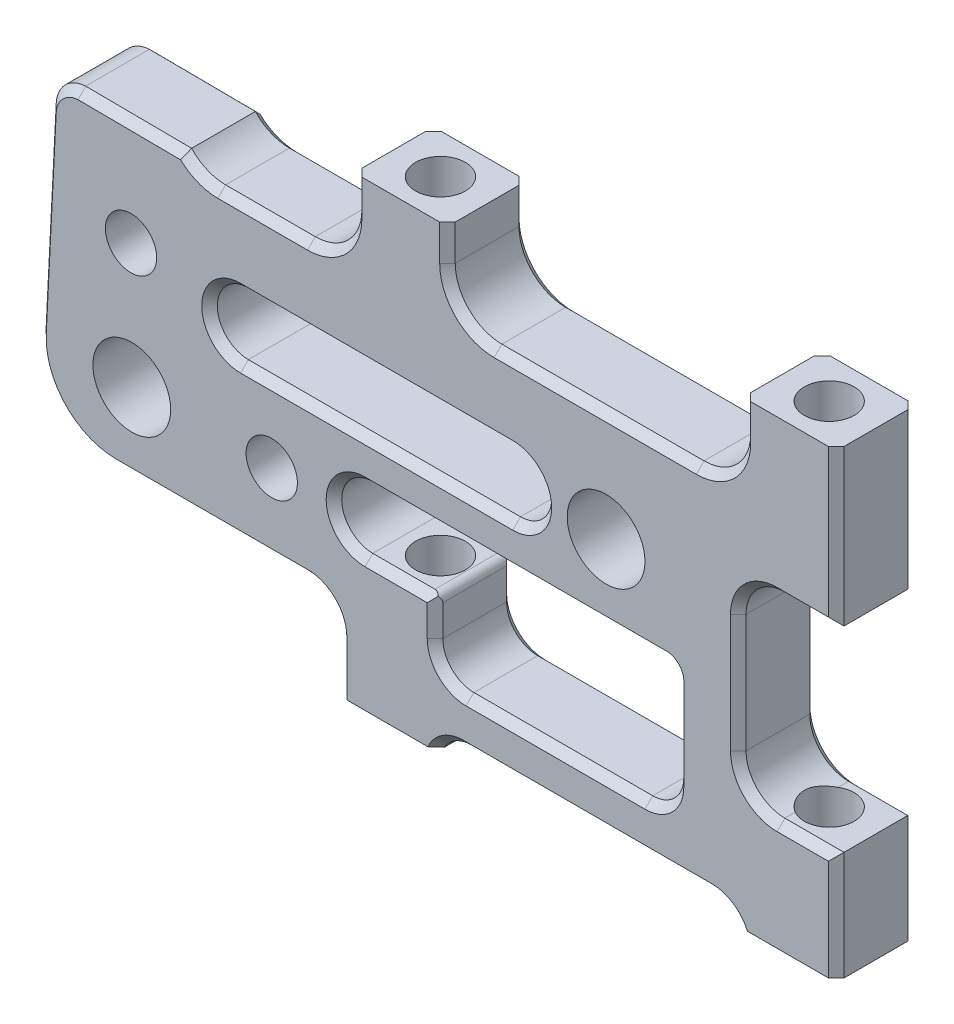
SolidWorks part; units mm, degrees
ref_plane "Front Plane" through (0, 0, 0) normal (0, 0, 1) x (1, 0, 0)
ref_plane "Top Plane" through (0, 0, 0) normal (0, 1, 0) x (1, 0, 0)
ref_plane "Right Plane" through (0, 0, 0) normal (1, 0, 0) x (0, 0, -1)
sketch "Sketch2" plane through (0, 0, 0) normal (0, 0, 1) x (1, 0, 0)
  line L22 (-33.9671, -1.5) -> (-46.3064, -1.5)
  line L23 (-51.3, 3.7538) -> (-50.6576, 16.3911)
  line L24 (-31, 22.6) -> (-25, 22.6)
  line L25 (0, 22.6) -> (0, 12.6)
  line L27 (0, 12.6) -> (-3.8, 12.6)
  line L29 (-31.9671, -3.5) -> (-31.9671, -7)
  line L31 (0, 0) -> (0, -7)
  line L32 (-31, 22.6) -> (-31, 20.2868)
  line L33 (-31, 22.6) -> (-25, 22.6)
  line L34 (-25, 22.6) -> (-25, 20.3)
  line L35 (-22, 17.3) -> (-9, 17.3)
  line L36 (-6, 20.3) -> (-6, 22.6)
  line L37 (-6, 22.6) -> (0, 22.6)
  line L38 (-6, 22.6) -> (0, 22.6)
  line L42 (-6.3, 10.1) -> (-6.3, 2.5)
  line L43 (-39.7653, 17.2868) -> (-34, 17.2868)
  line L44 (-3.8, 0) -> (0, 0)
  line L45 (-48.7653, 18.2868) -> (-41.9513, 18.2321)
  line L47 (-3, 22.6) -> (-3, -10.8306) construction
  line L51 (-28, 22.6) -> (-28, -7) construction
  line L53 (-23.9671, -6) -> (-8, -6)
  line L60 (-6.2679, -7) -> (0, -7)
  line L62 (-31.9671, -7) -> (-25.6991, -7)
  arc A0 (-31.9671, -3.5) -> (-33.9671, -1.5) centre (-33.9671, -3.5) ccw
  arc A1 (-48.7653, 18.2868) -> (-50.6576, 16.3911) centre (-48.6602, 16.2896) ccw
  arc A2 (-46.3064, -1.5) -> (-51.3, 3.7538) centre (-46.3064, 3.5) cw
  arc A3 (-6, 20.3) -> (-9, 17.3) centre (-9, 20.3) cw
  arc A4 (-22, 17.3) -> (-25, 20.3) centre (-22, 20.3) cw
  arc A5 (-39.7653, 17.2868) -> (-41.9513, 18.2321) centre (-39.7653, 20.2868) cw
  arc A6 (-34, 17.2868) -> (-31, 20.2868) centre (-34, 20.2868) ccw
  arc A7 (-3.8, 12.6) -> (-6.3, 10.1) centre (-3.8, 10.1) ccw
  arc A8 (-3.8, 0) -> (-6.3, 2.5) centre (-3.8, 2.5) cw
  arc A9 (-8, -6) -> (-6.2679, -7) centre (-8, -8) cw
  arc A10 (-23.9671, -6) -> (-25.6991, -7) centre (-23.9671, -8) ccw
  point P25 (-31.9671, -1.5)
  point P28 (-50.8206, 21)
  point P31 (-51.5671, -1.5)
  point P47 (-28, 22.6)
  point P48 (-3, 22.6)
  dimension "D13" = 2
  dimension "D14" = 5
  dimension "D15" = 3
  dimension "D16" = 3
  dimension "D18" = 2.5
  dimension "D6" = 2
  dimension "D2" = 5.3
  dimension "D3" = 5.5
  dimension "D4" = 19.6
  dimension "D5" = 6
  dimension "D7" = 10
  dimension "D9" = 45
  dimension "D11" = 6
  dimension "D17" = 7
  dimension "D19" = 25
  dimension "D22" = 51.3
extrude "Boss-Extrude1" add sketch "Sketch2" along normal blind 5.1
sketch "Sketch3" plane through (0, 0, 5.1) normal (0, 0, 1) x (1, 0, 0)
  line L0 (-39.7653, 17.2868) -> (-34, 17.2868) construction
  line L1 (-38.3, 12.2868) -> (-20.8, 12.2868)
  line L2 (-38.3, 12.2868) -> (-38.3, 8.2868)
  line L3 (-38.3, 8.2868) -> (-20.8, 8.2868)
  line L4 (-20.8, 12.2868) -> (-20.8, 8.2868)
  line L6 (-23.9671, -6) -> (-8, -6) construction
  line L7 (-6.3, 10.1) -> (-6.3, 2.5) construction
  line L8 (-30.3, 5.5) -> (-10.9063, 5.5)
  line L9 (-30.3, 1.5) -> (-25.8, 1.5)
  line L11 (-10.3, 4.8937) -> (-10.3, -1)
  line L12 (-12.3, -3) -> (-23.8, -3)
  line L13 (-25.8, -1) -> (-25.8, 1.5)
  circle A0 centre (-38.3, 10.2868) radius 2
  circle A1 centre (-20.8, 10.2868) radius 2
  arc A2 (-30.3, 5.5) -> (-30.3, 1.5) centre (-30.3, 3.5) ccw
  arc A3 (-10.3, 4.8937) -> (-10.9063, 5.5) centre (-10.9063, 4.8937) ccw
  arc A4 (-12.3, -3) -> (-10.3, -1) centre (-12.3, -1) ccw
  arc A5 (-23.8, -3) -> (-25.8, -1) centre (-23.8, -1) cw
  dimension "D7" = 2
  dimension "D9" = 2
  dimension "D1" = 4
  dimension "D2" = 17.5
  dimension "D3" = 5
  dimension "D4" = 32
  dimension "D5" = 19.3937
  dimension "D6" = 4
  dimension "D8" = 8.5
  dimension "D10" = 18
  dimension "D11" = 4.5
  dimension "D12" = 4
  dimension "D13" = 2.7868
  dimension "D14" = 3
extrude "Cut-Extrude1" cut sketch "Sketch3" against normal through all contours L2 A0 | L2 A0 | A1 L1 A0 L3 | L4 A1 | L4 A1 | A5 L12 A4 L11 A3 L8 A2 L9 L13
chamfer "Chamfer1" distance 0.5 angle 45 20 edges at (0, 17.6, 0) (-24.9671, -6.2679, 0) (-31.9671, -5.25, 0) (-32.5529, -2.0858, 0) (-40.1368, -1.5, 0) (-49.9306, 0.0554, 0) (-50.0757, 17.7025, 0) (-50.9788, 10.0725, 0) (-45.3583, 18.2595, 0) (-40.9561, 17.5333, 0) (-36.8827, 17.2868, 0) (-31, 21.4434, 0) (-31.8787, 18.1655, 0) (-25, 21.45, 0) (-24.1213, 18.1787, 0) (-6, 21.45, 0) (-15.5, 17.3, 0) (-6.8787, 18.1787, 0) (-7, -6.2679, 0) (-15.9835, -6, 0)
chamfer "Chamfer2" distance 0.5 angle 45 13 edges at (-25.8, 0.25, 0) (-25.2142, -2.4142, 0) (-18.05, -3, 0) (-10.8858, -2.4142, 0) (-28.05, 1.5, 0) (-10.3, 1.9468, 0) (-32.3, 3.5, 0) (-10.4776, 5.3224, 0) (-20.6032, 5.5, 0) (-29.55, 12.2868, 0) (-40.3, 10.2868, 0) (-18.8, 10.2868, 0) (-29.55, 8.2868, 0)
chamfer "Chamfer3" distance 0.5 angle 45 25 edges at (-24.9671, -6.2679, 5.1) (-1.9, 0, 5.1) (-5.5678, 0.7322, 5.1) (-1.9, 12.6, 5.1) (-6.3, 6.3, 5.1) (-5.5678, 11.8678, 5.1) (0, 17.6, 5.1) (-6, 21.45, 5.1) (-6.8787, 18.1787, 5.1) (-15.5, 17.3, 5.1) (-25, 21.45, 5.1) (-24.1213, 18.1787, 5.1) (-31.9671, -5.25, 5.1) (-32.5529, -2.0858, 5.1) (-40.1368, -1.5, 5.1) (-49.9306, 0.0554, 5.1) (-50.9788, 10.0725, 5.1) (-50.0757, 17.7025, 5.1) (-45.3583, 18.2595, 5.1) (-31, 21.4434, 5.1) (-40.9561, 17.5333, 5.1) (-31.8787, 18.1655, 5.1) (-36.8827, 17.2868, 5.1) (-7, -6.2679, 5.1) (-15.9835, -6, 5.1)
chamfer "Chamfer4" distance 0.5 angle 45 1 edges at (0, -3.75, 5.1)
chamfer "Chamfer5" distance 0.5 angle 45 8 edges at (-25.8, 0.25, 5.1) (-25.2142, -2.4142, 5.1) (-18.05, -3, 5.1) (-10.8858, -2.4142, 5.1) (-10.3, 1.9468, 5.1) (-32.3, 3.5, 5.1) (-10.4776, 5.3224, 5.1) (-20.6032, 5.5, 5.1)
fillet "Fillet1" radius 0.5 1 edges at (-25.8, 1.5, 2.55)
sketch "Sketch4" plane through (0, 0, 5.1) normal (0, 0, 1) x (1, 0, 0)
  line L0 (-6.3, 10.1) -> (-6.3, 2.5) construction
  line L3 (-30.3, 3.5) -> (-40.304, 3.5) construction
  line L4 (-6.8, 2.5) -> (-6.8, 10.1) construction
  line L6 (0, 22.6) -> (0, 12.6) construction
  line L8 (-0.5, -7) -> (-0.5, -0.5) construction
  circle A0 centre (-14.8, 10.2868) radius 2.5
  circle A1 centre (-45.3, 3.5) radius 2.5
  arc A2 (-30.3, 5.5) -> (-30.3, 1.5) centre (-30.3, 3.5) ccw construction
  arc A3 (-30.3, 5.5) -> (-30.3, 1.5) centre (-30.3, 3.5) ccw
  circle A4 centre (-36.3, 3.5) radius 1.65
  circle A5 centre (-45.35, 11.5) radius 1.65
  point P12 (-20.8, 10.2868)
  dimension "D1" = 5
  dimension "D4" = 5
  dimension "D6" = 3.3
  dimension "D8" = 3.3
  dimension "D2" = 8.5
  dimension "D5" = 38.5
  dimension "D7" = 9
  dimension "D9" = 45.35
  dimension "D10" = 50.3006
  dimension "D11" = 8
extrude "Cut-Extrude2" cut sketch "Sketch4" against normal through all contours A5 | A0 | A1 | A4 L3 | L3 A4
sketch "Sketch5" plane through (0, 22.6, 0) normal (0, 1, 0) x (1, 0, 0)
  line L0 (-31, -2.55) -> (-25, -2.55) construction
  line L1 (-31, -4.6) -> (-31, -0.5) construction
  line L2 (-25, -4.6) -> (-25, -0.5) construction
  circle A0 centre (-28, -2.55) radius 1.6
  dimension "D1" = 3.2
extrude "Cut-Extrude4" cut sketch "Sketch5" against normal up to surface (10.3132 mm away) up to face at (-29.55, 12.2868, 2.55)
sketch "Sketch6" plane through (0, 22.6, 0) normal (0, 1, 0) x (1, 0, 0)
  line L0 (-6, -2.55) -> (0, -2.55) construction
  line L1 (-6, -4.6) -> (-6, -0.5) construction
  line L2 (0, -4.6) -> (0, -0.5) construction
  circle A0 centre (-3, -2.55) radius 1.6
  dimension "D1" = 3.2
extrude "Cut-Extrude5" cut sketch "Sketch6" against normal through all
sketch "Sketch7" plane through (0, -7, 0) normal (0, -1, 0) x (1, 0, 0)
  line L0 (-31.9671, 2.55) -> (-25.6991, 2.55) construction
  line L1 (-31.9671, 4.6) -> (-31.9671, 0.5) construction
  line L2 (-25.6991, 4.6) -> (-25.6991, 0.5) construction
  line L3 (-28, 0) -> (-28, 5.1) construction
  line L4 (-31.4671, 5.1) -> (-26.2584, 5.1) construction
  circle A0 centre (-28, 2.55) radius 1.6
  dimension "D1" = 3.2
extrude "Cut-Extrude6" cut sketch "Sketch7" against normal up to surface (8.5 mm away)
